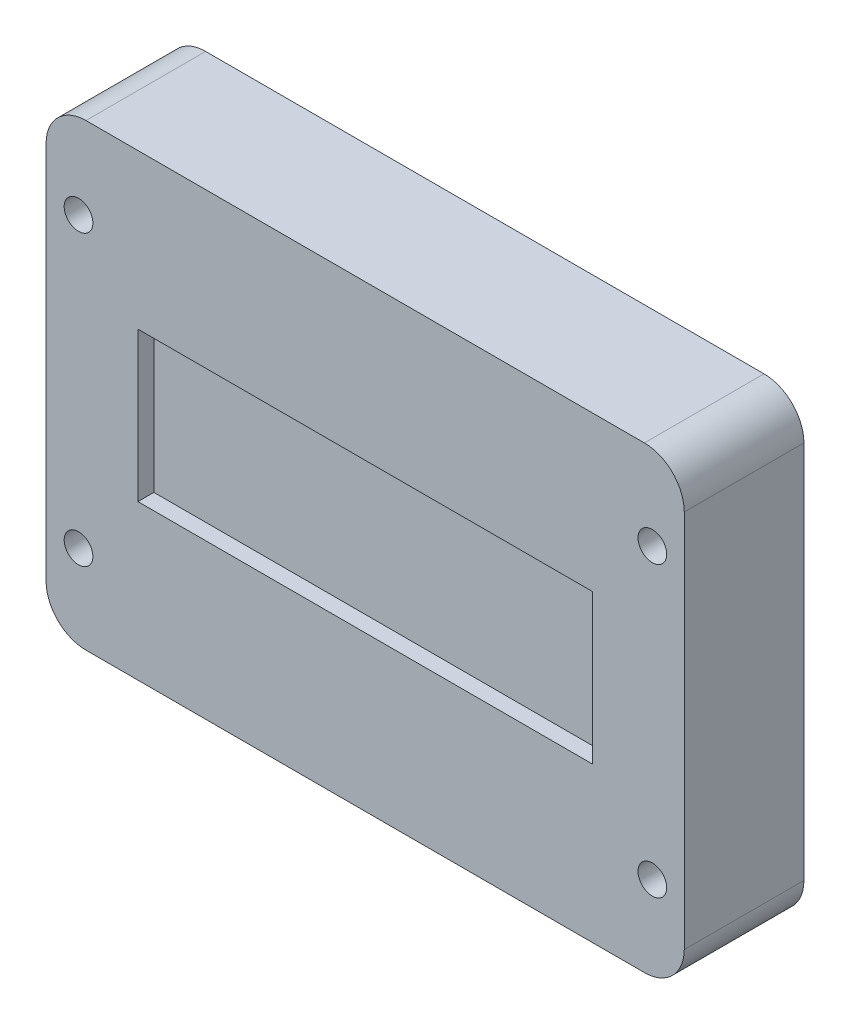
SolidWorks part; units mm, degrees
ref_plane "Front Plane" through (0, 0, 0) normal (0, 0, 1) x (1, 0, 0)
ref_plane "Top Plane" through (0, 0, 0) normal (0, 1, 0) x (1, 0, 0)
ref_plane "Right Plane" through (0, 0, 0) normal (1, 0, 0) x (0, 0, -1)
sketch "Sketch1" plane through (0, 0, 0) normal (0, 0, 1) x (1, 0, 0)
  line L0 (-50.8, 22.9235) -> (50.8, 22.9235) construction
  line L1 (-44.45, -36.5125) -> (44.45, -36.5125)
  line L2 (-50.8, -30.1625) -> (-50.8, 30.1625)
  line L3 (-44.45, 36.5125) -> (44.45, 36.5125)
  line L4 (50.8, -30.1625) -> (50.8, 30.1625)
  line L5 (-50.8, -36.5125) -> (50.8, 36.5125) construction
  line L6 (-50.8, 36.5125) -> (50.8, -36.5125) construction
  line L7 (-50.8, -23.0505) -> (50.8, -23.0505) construction
  line L8 (45.72, 36.5125) -> (45.72, -36.5125) construction
  line L9 (-45.6321, -36.5125) -> (-45.6321, 36.5125) construction
  circle A0 centre (-45.6321, 22.9235) radius 2.286
  circle A1 centre (45.72, 22.9235) radius 2.286
  circle A2 centre (45.72, -23.0505) radius 2.286
  circle A3 centre (-45.6321, -23.0505) radius 2.286
  arc A4 (44.45, 36.5125) -> (50.8, 30.1625) centre (44.45, 30.1625) cw
  arc A5 (50.8, -30.1625) -> (44.45, -36.5125) centre (44.45, -30.1625) cw
  arc A6 (-50.8, -30.1625) -> (-44.45, -36.5125) centre (-44.45, -30.1625) ccw
  arc A7 (-50.8, 30.1625) -> (-44.45, 36.5125) centre (-44.45, 30.1625) cw
  point P0 (0, 0)
  dimension "D3" = 4.572
  dimension "D8" = 6.35
  dimension "D1" = 101.6
  dimension "D2" = 73.025
  dimension "D4" = 13.589
  dimension "D5" = 45.974
  dimension "D6" = 5.08
  dimension "D7" = 91.3521
extrude "Boss-Extrude1" add sketch "Sketch1" along normal blind 19.05
sketch "Sketch2" plane through (0, 0, 19.05) normal (0, 0, 1) x (1, 0, 0)
  line L1 (-36.1754, -11.8928) -> (36.1754, -11.8928)
  line L2 (-36.1754, -11.8928) -> (-36.1754, 11.8928)
  line L3 (-36.1754, 11.8928) -> (36.1754, 11.8928)
  line L4 (36.1754, -11.8928) -> (36.1754, 11.8928)
  line L5 (-36.1754, -11.8928) -> (36.1754, 11.8928) construction
  line L6 (-36.1754, 11.8928) -> (36.1754, -11.8928) construction
  point P0 (0, 0)
extrude "Cut-Extrude1" cut sketch "Sketch2" against normal blind 2.54
